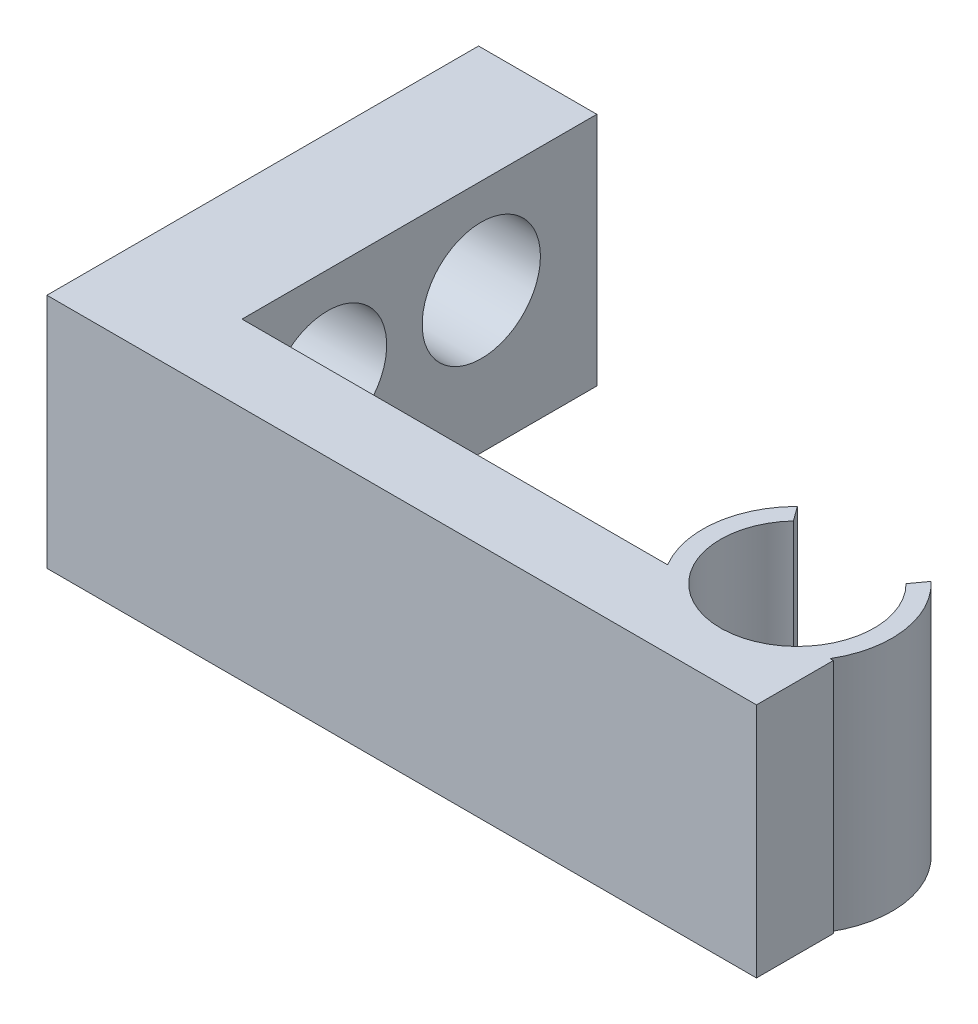
SolidWorks part; units mm, degrees
ref_plane "前基準面" through (0, 0, 0) normal (0, 0, 1) x (1, 0, 0)
ref_plane "上基準面" through (0, 0, 0) normal (0, 1, 0) x (1, 0, 0)
ref_plane "右基準面" through (0, 0, 0) normal (1, 0, 0) x (0, 0, -1)
sketch "草圖1" plane through (0, 0, 0) normal (0, 1, 0) x (1, 0, 0)
  line L0 (18.0905, 11.7799) -> (17.1953, 13.0121)
  line L1 (30, -3.25) -> (-30, -3.25)
  line L2 (30, -3.25) -> (30, 3.25)
  line L3 (30, 3.25) -> (27.8917, 3.25)
  line L4 (-30, -3.25) -> (-30, 3.25)
  line L5 (0, 0.8553) -> (0, -3.25) construction
  line L6 (30, 0) -> (-30, 0) construction
  line L7 (27.4483, 11.9515) -> (28.3389, 13.1772)
  line L8 (4.4372, 3.25) -> (18.1699, 3.25)
  line L9 (-5.0395, 3.25) -> (-30, 3.25)
  line L10 (-5.0395, 3.25) -> (4.4372, 3.25)
  line L11 (11.3035, 17.1456) -> (11.3035, 7.3553) construction
  arc A0 (18.0905, 11.7799) -> (27.4483, 11.9515) centre (22.8521, 7.3553) ccw
  arc A1 (17.1953, 13.0121) -> (28.3389, 13.1772) centre (22.8521, 7.3553) ccw
  point P0 (0, 0)
  dimension "D1" = 13
  dimension "D2" = 16
  dimension "D3" = 36
  dimension "D4" = 36
  dimension "D5" = 6.5
  dimension "D6" = 60
extrude "填料-伸長1" add sketch "草圖1" along normal blind 20 contours L3 A1 A0 | L0 A1 L3 A0 | L3 A1 L7 A0 | A1 L3 L4 L1 L2
sketch "草圖2" plane through (0, 0, -3.25) normal (0, 0, -1) x (-1, 0, 0)
  line L0 (20, 20) -> (30, 20)
  line L1 (20, 20) -> (20, 0.0999)
  line L2 (30, 20) -> (30, 0.0999)
  line L3 (20, 0.0999) -> (30, 0.0999)
  line L4 (30, 20) -> (-15.9858, 20) construction
  dimension "D1" = 10
extrude "填料-伸長2" add sketch "草圖2" along normal blind 30
sketch "草圖3" plane through (-20, 0, 0) normal (1, 0, 0) x (0, 0, -1)
  line L0 (16.9817, 10.0398) -> (16.9817, 2.3951) construction
  circle A0 centre (23.4817, 11.9914) radius 2.5
  circle A1 centre (10.4817, 11.9914) radius 2.5
  dimension "D1" = 5
  dimension "D2" = 6.5
extrude "除料-伸長1" cut sketch "草圖3" against normal blind 15 contours A1 | A0
sketch "草圖6" plane through (-20, 0, 0) normal (1, 0, 0) x (0, 0, -1)
  line L0 (10.4817, 11.9914) -> (23.4817, 11.9914) construction
  line L1 (16.9817, 11.9914) -> (16.9817, 6.1887) construction
  circle A2 centre (23.4817, 11.9914) radius 5
  circle A3 centre (10.4817, 11.9914) radius 5
  dimension "D1" = 10
extrude "除料-伸長3" cut sketch "草圖6" against normal blind 9
